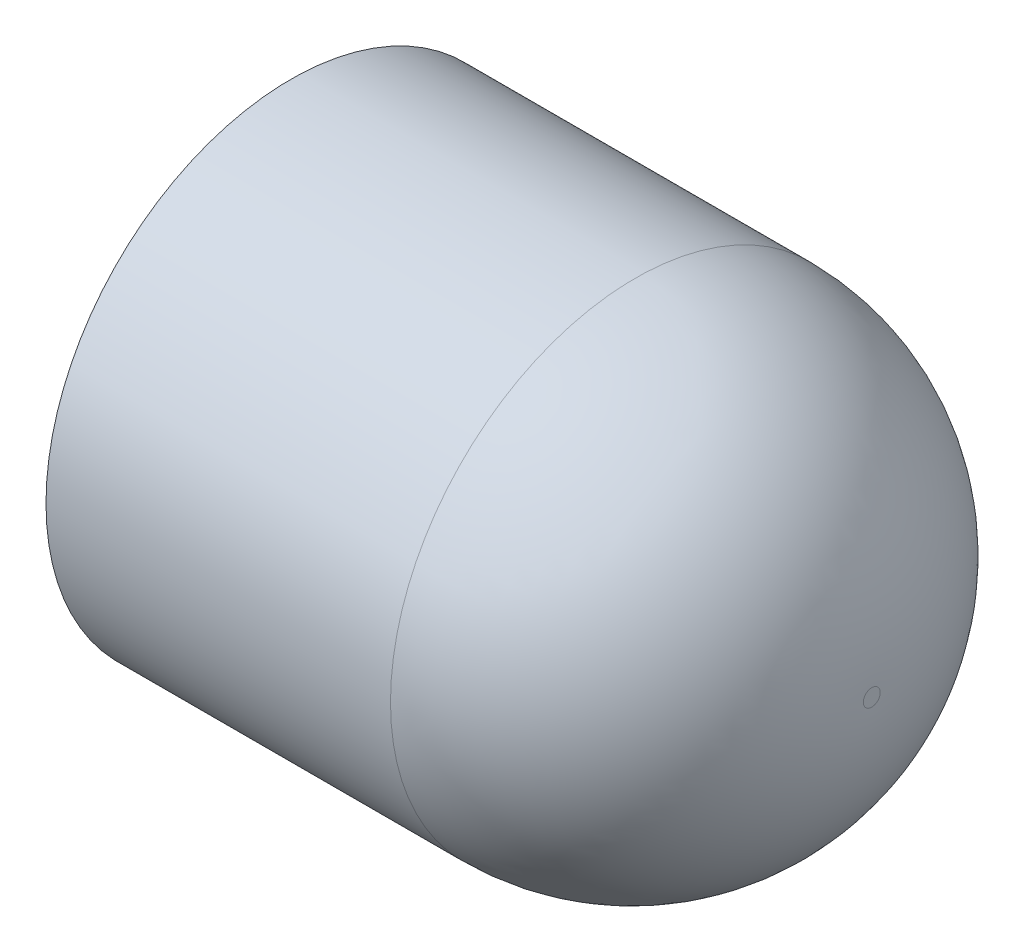
SolidWorks part; units mm, degrees
ref_plane "Front Plane" through (0, 0, 0) normal (0, 0, 1) x (1, 0, 0)
ref_plane "Top Plane" through (0, 0, 0) normal (0, 1, 0) x (1, 0, 0)
ref_plane "Right Plane" through (0, 0, 0) normal (1, 0, 0) x (0, 0, -1)
sketch "Sketch1" plane through (0, 0, 0) normal (0, 1, 0) x (1, 0, 0)
  line L1 (0, 0) -> (21.844, 0)
  line L2 (0, 0) -> (0, 9.2075)
  line L3 (0, 9.2075) -> (12.954, 9.2075)
  line L4 (21.844, 0) -> (21.844, 0.3175)
  arc A0 (12.954, 9.2075) -> (21.844, 0.3175) centre (12.954, 0.3175) cw
  dimension "D2" = 8.89
  dimension "D1" = 9.2075
  dimension "D3" = 21.844
revolve "Revolve1" add sketch "Sketch1" angle 360 about L1
sketch "Sketch2" plane through (0, 0, 0) normal (-1, 0, 0) x (0, 0, 1)
  line L0 (-9.2075, 0) -> (9.2075, 0)
  circle A0 centre (0, 0) radius 9.2075 construction
